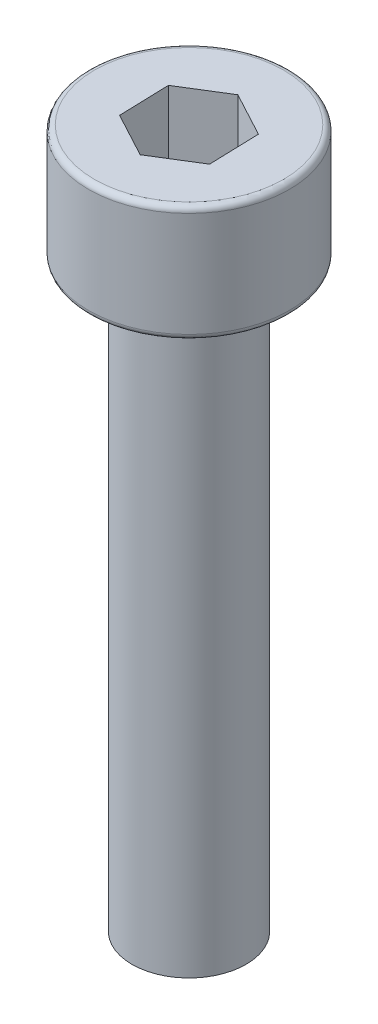
SolidWorks part; units mm, degrees
ref_plane "Front Plane" through (0, 0, 0) normal (0, 0, 1) x (1, 0, 0)
ref_plane "Top Plane" through (0, 0, 0) normal (0, 1, 0) x (1, 0, 0)
ref_plane "Right Plane" through (0, 0, 0) normal (1, 0, 0) x (0, 0, -1)
sketch "Sketch1" plane through (0, 0, 0) normal (0, 1, 0) x (1, 0, 0)
  circle A0 centre (0, 0) radius 1.96
  dimension "D1" = 3.92
extrude "Boss-Extrude1" add sketch "Sketch1" along normal blind 20
sketch "Sketch2" plane through (0, 20, 0) normal (0, 1, 0) x (1, 0, 0)
  circle A0 centre (0, 0) radius 3.45
  dimension "D1" = 6.9
extrude "Boss-Extrude2" add sketch "Sketch2" along normal blind 4
sketch "Sketch3" plane through (0, 24, 0) normal (0, 1, 0) x (1, 0, 0)
  line L1 (-0.0536, 1.7312) -> (-1.5261, 0.8192)
  line L2 (-1.5261, 0.8192) -> (-1.4725, -0.912)
  line L3 (-1.4725, -0.912) -> (0.0536, -1.7312)
  line L4 (0.0536, -1.7312) -> (1.5261, -0.8192)
  line L5 (1.5261, -0.8192) -> (1.4725, 0.912)
  line L6 (1.4725, 0.912) -> (-0.0536, 1.7312)
  circle A0 centre (0, 0) radius 1.5 construction
  dimension "D1" = 3
extrude "Cut-Extrude1" cut sketch "Sketch3" against normal blind 2.7
fillet "Fillet1" radius 0.2 2 edges at (0, 24, 3.45) (0, 20, 3.45)
